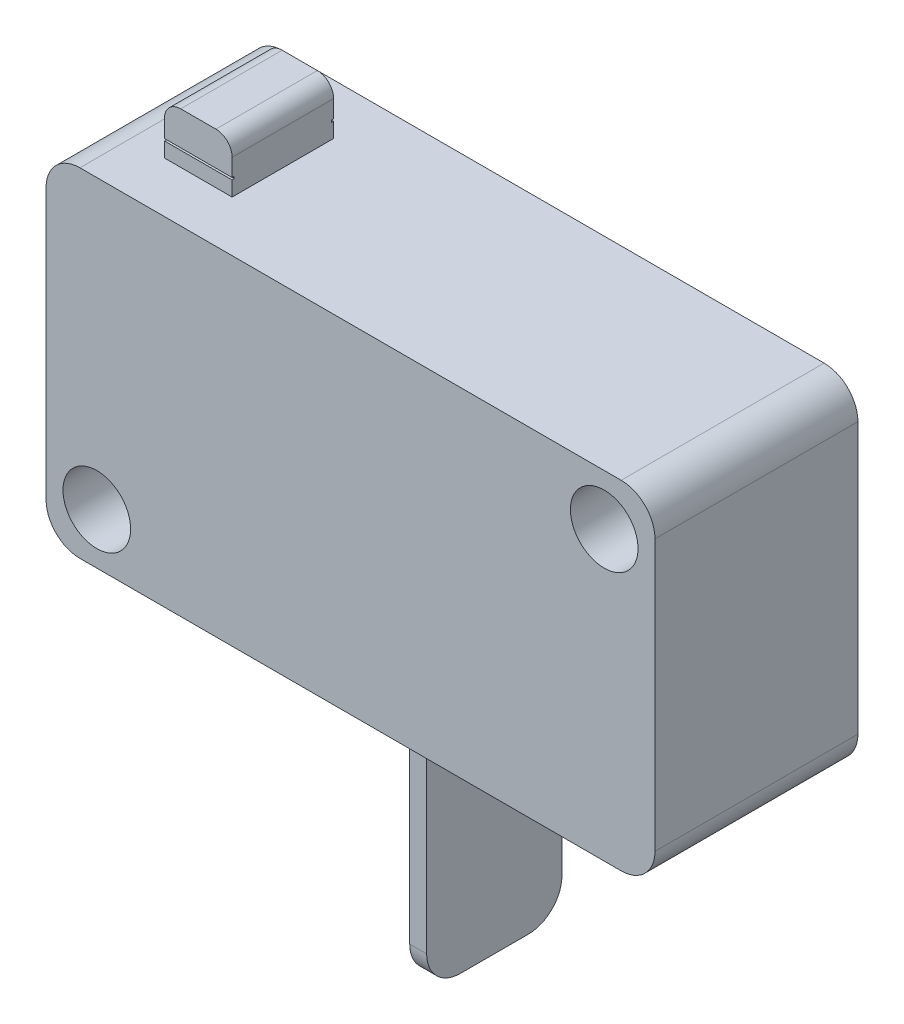
SolidWorks part; units mm, degrees
ref_plane "Front Plane" through (0, 0, 0) normal (0, 0, 1) x (1, 0, 0)
ref_plane "Top Plane" through (0, 0, 0) normal (0, 1, 0) x (1, 0, 0)
ref_plane "Right Plane" through (0, 0, 0) normal (1, 0, 0) x (0, 0, -1)
sketch "Sketch1" plane through (0, 0, 0) normal (0, 0, 1) x (1, 0, 0)
  line L1 (14.2875, -7.9375) -> (-14.2875, -7.9375)
  line L2 (14.2875, -7.9375) -> (14.2875, 7.9375)
  line L3 (14.2875, 7.9375) -> (-14.2875, 7.9375)
  line L4 (-14.2875, -7.9375) -> (-14.2875, 7.9375)
  line L5 (14.2875, -7.9375) -> (-14.2875, 7.9375) construction
  line L6 (14.2875, 7.9375) -> (-14.2875, -7.9375) construction
  circle A0 centre (11.9062, 5.5563) radius 1.5875
  circle A1 centre (-11.9063, -5.5563) radius 1.5875
  point P0 (0, 0)
  dimension "D3" = 3.175
  dimension "D4" = 3.175
  dimension "D1" = 28.575
  dimension "D2" = 15.875
  dimension "D5" = 2.3813
  dimension "D6" = 2.3813
  dimension "D7" = 2.3813
  dimension "D8" = 2.3813
extrude "Boss-Extrude1" add sketch "Sketch1" along normal blind 9.525
fillet "Fillet1" radius 1.5875 4 edges at (-14.2875, 7.9375, 4.7625) (14.2875, -7.9375, 4.7625) (14.2875, 7.9375, 4.7625) (-14.2875, -7.9375, 4.7625)
sketch "Sketch2" plane through (0, 7.9375, 0) normal (0, 1, 0) x (1, 0, 0)
  line L0 (-12.7, -4.7625) -> (12.7, -4.7625) construction
  line L1 (-12.7, 0) -> (-12.7, -9.525) construction
  line L2 (12.7, -9.525) -> (12.7, 0) construction
  line L3 (-14.2875, -9.525) -> (-14.2875, 0) construction
  line L4 (-7.9375, -7.1438) -> (-11.1125, -7.1438)
  line L5 (-7.9375, -7.1438) -> (-7.9375, -2.3813)
  line L6 (-7.9375, -2.3813) -> (-11.1125, -2.3813)
  line L7 (-11.1125, -7.1438) -> (-11.1125, -2.3813)
  line L8 (-7.9375, -7.1438) -> (-11.1125, -2.3813) construction
  line L9 (-7.9375, -2.3813) -> (-11.1125, -7.1438) construction
  point P6 (-9.525, -4.7625)
  dimension "D1" = 3.175
  dimension "D2" = 4.7625
  dimension "D3" = 4.7625
extrude "Boss-Extrude2" add sketch "Sketch2" along normal blind 2.3813
fillet "Fillet2" radius 0.762 2 edges at (-7.9375, 10.3187, 4.7625) (-11.1125, 10.3187, 4.7625)
sketch "Sketch3" plane through (0, -7.9375, 0) normal (0, -1, 0) x (-1, 0, 0)
  line L0 (14.2875, -4.7625) -> (-14.2875, -4.7625) construction
  line L1 (14.2875, 0) -> (14.2875, -9.525) construction
  line L2 (-14.2875, -9.525) -> (-14.2875, 0) construction
  line L4 (-1.9844, -1.5875) -> (-1.1906, -1.5875)
  line L5 (-1.9844, -1.5875) -> (-1.9844, -7.9375)
  line L6 (-1.9844, -7.9375) -> (-1.1906, -7.9375)
  line L7 (-1.1906, -1.5875) -> (-1.1906, -7.9375)
  line L8 (-1.9844, -1.5875) -> (-1.1906, -7.9375) construction
  line L9 (-1.9844, -7.9375) -> (-1.1906, -1.5875) construction
  point P6 (-1.5875, -4.7625)
  dimension "D1" = 15.875
  dimension "D2" = 6.35
  dimension "D3" = 0.7937
extrude "Boss-Extrude3" add sketch "Sketch3" along normal blind 11.1125
fillet "Fillet3" radius 1.5875 2 edges at (1.5875, -19.05, 1.5875) (1.5875, -19.05, 7.9375)
sketch "Sketch4" plane through (0, 0, 7.1437) normal (0, 0, 1) x (1, 0, 0)
  line L0 (-11.1125, 9.5567) -> (-11.1125, 7.9375) construction
  line L1 (-11.1125, 8.632) -> (-7.9375, 8.632)
  line L2 (-11.1125, 8.632) -> (-11.1125, 8.7312)
  line L3 (-11.1125, 8.7312) -> (-7.9375, 8.7312)
  line L4 (-7.9375, 8.632) -> (-7.9375, 8.7312)
  line L5 (-7.9375, 9.5567) -> (-7.9375, 7.9375) construction
  line L6 (-11.1125, 7.9375) -> (-7.9375, 7.9375) construction
  dimension "D1" = 0.0992
  dimension "D2" = 0.7937
extrude "Cut-Extrude1" cut sketch "Sketch4" against normal blind 0.0992
sketch "Sketch5" plane through (-11.1125, 0, 0) normal (-1, 0, 0) x (0, 0, 1)
  line L0 (4.7625, 9.5568) -> (4.7625, 7.9375) construction
  line L1 (7.1438, 9.5568) -> (2.3813, 9.5568) construction
  line L2 (2.3813, 7.9375) -> (7.1438, 7.9375) construction
ref_plane "Plane1" through (0, 0, 4.7625) normal (0, 0, 1) x (1, 0, 0)
mirror "Mirror1" about plane through (0, 0, 4.7625) normal (0, 0, 1) of "Cut-Extrude1"
